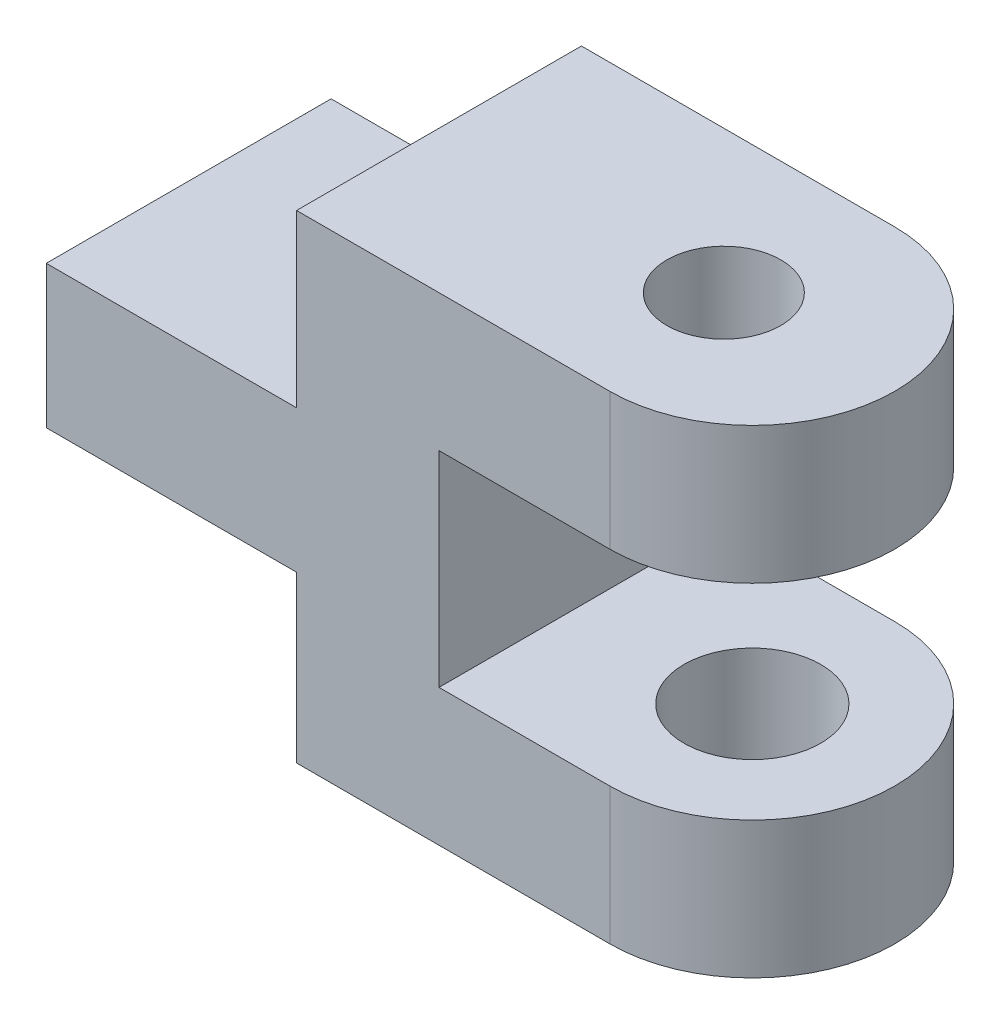
SolidWorks part; units mm, degrees
ref_plane "Front Plane" through (0, 0, 0) normal (0, 0, 1) x (1, 0, 0)
ref_plane "Top Plane" through (0, 0, 0) normal (0, 1, 0) x (1, 0, 0)
ref_plane "Right Plane" through (0, 0, 0) normal (1, 0, 0) x (0, 0, -1)
sketch "Sketch1" plane through (0, 0, 0) normal (0, 0, 1) x (1, 0, 0)
  line L0 (0, 0) -> (21.9697, 0)
  line L1 (21.9697, 0) -> (21.9697, -14.5)
  line L2 (21.9697, -14.5) -> (49.4697, -14.5)
  line L3 (49.4697, -14.5) -> (49.4697, -2.5)
  line L4 (49.4697, -2.5) -> (34.4697, -2.5)
  line L5 (34.4697, -2.5) -> (34.4697, 15.5)
  line L6 (34.4697, 15.5) -> (49.4697, 15.5)
  line L7 (49.4697, 15.5) -> (49.4697, 27.5)
  line L8 (49.4697, 27.5) -> (21.9697, 27.5)
  line L9 (21.9697, 27.5) -> (21.9697, 12.5)
  line L10 (21.9697, 12.5) -> (0, 12.5)
  line L11 (0, 12.5) -> (0, 0)
  dimension "D1" = 12.5
  dimension "D2" = 18
  dimension "D3" = 12
  dimension "D4" = 12
  dimension "D5" = 15
  dimension "D6" = 27.5
  dimension "D7" = 15
  dimension "D8" = 27.5
  dimension "D9" = 15
extrude "Boss-Extrude1" add sketch "Sketch1" along normal blind 25
sketch "Sketch2" plane through (0, 27.5, 0) normal (0, 1, 0) x (1, 0, 0)
  line L0 (49.4697, -25) -> (49.4697, 0) construction
  circle A0 centre (49.4697, -12.5) radius 12.5
  dimension "D1" = 25
extrude "Boss-Extrude2" add sketch "Sketch2" against normal blind 12
sketch "Sketch3" plane through (0, -2.5, 0) normal (0, 1, 0) x (1, 0, 0)
  line L0 (49.4697, -25) -> (49.4697, 0) construction
  circle A0 centre (49.4697, -12.5) radius 12.5
  dimension "D1" = 25
extrude "Boss-Extrude3" add sketch "Sketch3" against normal blind 12
sketch "Sketch4" plane through (0, 27.5, 0) normal (0, 1, 0) x (1, 0, 0)
  circle A0 centre (46.9697, -12.5) radius 5
  point P8 (48.7818, -22.9283)
  dimension "D1" = 10
extrude "Cut-Extrude1" cut sketch "Sketch4" against normal blind 12
sketch "Sketch5" plane through (0, -2.5, 0) normal (0, 1, 0) x (1, 0, 0)
  circle A0 centre (49.4697, -12.5) radius 6
  arc A1 (49.4697, -25) -> (49.4697, 0) centre (49.4697, -12.5) ccw construction
  point P6 (61.9697, -12.5)
  dimension "D1" = 12
  dimension "D2" = 12.5
extrude "Cut-Extrude2" cut sketch "Sketch5" against normal blind 12 contours A0
